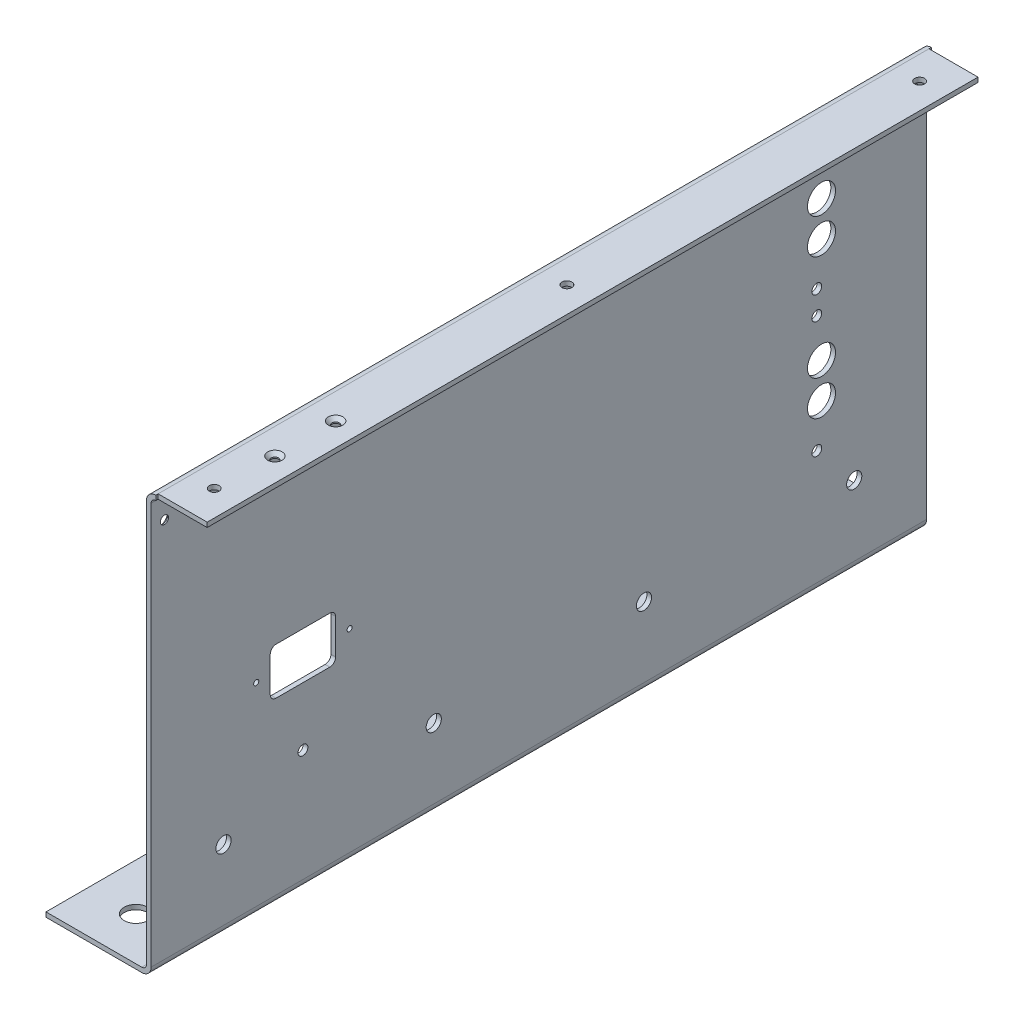
SolidWorks part; units mm, degrees
ref_plane "Спереди" through (0, 0, 0) normal (0, 0, 1) x (1, 0, 0)
ref_plane "Сверху" through (0, 0, 0) normal (0, 1, 0) x (1, 0, 0)
ref_plane "Справа" through (0, 0, 0) normal (1, 0, 0) x (0, 0, -1)
sketch "Эскиз1" plane through (0, 0, 0) normal (0, 0, 1) x (1, 0, 0)
  line L0 (0, 0) -> (0, 82.8028) construction
  line L1 (-1, -68) -> (-1, 104)
  line L4 (1, -68) -> (1, 104)
  line L5 (0, 0) -> (50.6989, 0) construction
  line L6 (3, 106) -> (24, 106)
  line L7 (3, 108) -> (24, 108)
  line L9 (-3, -72) -> (-44, -72)
  line L10 (24, 108) -> (24, 106)
  line L12 (-3, -70) -> (-44, -70)
  line L13 (-44, -72) -> (-44, -70)
  arc A0 (3, 106) -> (1, 104) centre (3, 104) ccw
  arc A1 (-3, -70) -> (-1, -68) centre (-3, -68) ccw
  arc A2 (-3, -72) -> (1, -68) centre (-3, -68) ccw
  arc A3 (-1, 104) -> (3, 108) centre (3, 104) cw
  dimension "D7" = 2
  dimension "D8" = 4
  dimension "D1" = 2
  dimension "D2" = 180
  dimension "D3" = 2
  dimension "D4" = 25
  dimension "D5" = 45
  dimension "D6" = 2
extrude "Вытянуть1" add sketch "Эскиз1" along normal blind 332
sketch "Эскиз2" plane through (-1, 0, 0) normal (-1, 0, 0) x (0, 0, 1)
  line L0 (-8.3976, -38) -> (341.3976, -38) construction
  line L1 (332, -72) -> (0, -72) construction
  line L2 (166, 127.3322) -> (166, -99.1297) construction
  line L3 (0, 104) -> (0, -68) construction
  line L4 (332, 104) -> (332, -68) construction
  circle A0 centre (31, -38) radius 3.25
  circle A1 centre (121, -38) radius 3.25
  circle A2 centre (211, -38) radius 3.25
  circle A3 centre (301, -38) radius 3.25
  dimension "D2" = 90
  dimension "D4" = 6.5
  dimension "D1" = 34
  dimension "D3" = 31
extrude "Вырез-Вытянуть1" cut sketch "Эскиз2" against normal blind 5
sketch "Эскиз3" plane through (0, -70, 0) normal (0, 1, 0) x (1, 0, 0)
  line L0 (-79.1329, -166) -> (76.6618, -166) construction
  line L1 (-24, 28.7881) -> (-24, -351.4381) construction
  line L4 (-44, -332) -> (-44, 0) construction
  line L5 (-3, 0) -> (-44, 0) construction
  line L6 (-3, -332) -> (-44, -332) construction
  circle A0 centre (-24, -18.5) radius 5
  circle A1 centre (-24, -313.5) radius 5
  dimension "D2" = 295
  dimension "D3" = 10
  dimension "D1" = 20
extrude "Вырез-Вытянуть2" cut sketch "Эскиз3" against normal blind 5
sketch "Эскиз4" plane through (0, 108, 0) normal (0, 1, 0) x (1, 0, 0)
  line L0 (-77.123, -166) -> (75.0406, -166) construction
  line L1 (24, 0) -> (3, 0) construction
  line L2 (24, -332) -> (3, -332) construction
  line L3 (3, -332) -> (3, 0) construction
  line L4 (3, -1) -> (29.1791, -1)
  line L5 (3, -1) -> (3, 2.2573)
  line L6 (3, 2.2573) -> (29.1791, 2.2573)
  line L7 (29.1791, -1) -> (29.1791, 2.2573)
  line L8 (24, -332) -> (24, 0) construction
  line L9 (29.1791, -331) -> (29.1791, -334.2573)
  line L10 (3, -334.2573) -> (29.1791, -334.2573)
  line L11 (3, -331) -> (3, -334.2573)
  line L12 (3, -331) -> (29.1791, -331)
  dimension "D1" = 1
  dimension "D2" = 21
extrude "Вырез-Вытянуть3" cut sketch "Эскиз4" against normal blind 10
sketch "Эскиз5" plane through (-1, 0, 0) normal (-1, 0, 0) x (0, 0, 1)
  line L0 (331, 108) -> (1, 108) construction
  line L1 (0, 104) -> (0, -68) construction
  line L2 (166, -112.0097) -> (166, 140.7956) construction
  line L3 (332, 104) -> (332, -68) construction
  circle A0 centre (5.7, 95) radius 1.75
  circle A1 centre (326.3, 95) radius 1.75
  dimension "D1" = 13
  dimension "D3" = 3.5
  dimension "D2" = 5.7
extrude "Вырез-Вытянуть4" cut sketch "Эскиз5" against normal blind 2.5
chamfer "Фаска1" distance 1.5 angle 45 2 edges at (-1, 96.75, 326.3) (-1, 93.25, 5.7)
sketch "Эскиз6" plane through (-1, 0, 0) normal (-1, 0, 0) x (0, 0, 1)
  line L0 (47, 93.2316) -> (47, -25.0596) construction
  line L1 (0, 104) -> (0, -68) construction
  line L2 (332, -70) -> (0, -70) construction
  line L3 (64.8276, 6) -> (25.4985, 6) construction
  line L4 (64.8276, 66) -> (25.4985, 66) construction
  line L5 (45, -11.328) -> (45, 71.6756) construction
  circle A0 centre (47, 91) radius 2.1
  circle A1 centre (47, 41) radius 2.1
  circle A2 centre (47, 31) radius 2.1
  circle A3 centre (47, -19) radius 2.1
  circle A4 centre (45, -1.5) radius 6
  circle A5 centre (45, 58.5) radius 6
  circle A6 centre (45, 13.5) radius 6
  circle A7 centre (45, 73.5) radius 6
  dimension "D2" = 50
  dimension "D3" = 50
  dimension "D5" = 10
  dimension "D6" = 4.2
  dimension "D8" = 7.5
  dimension "D9" = 7.5
  dimension "D10" = 12
  dimension "D1" = 47
  dimension "D4" = 161
  dimension "D7" = 2
extrude "Вырез-Вытянуть5" cut sketch "Эскиз6" against normal blind 10
cosmetic thread "Условное изображение резьбы1"
cosmetic thread "Условное изображение резьбы2"
cosmetic thread "Условное изображение резьбы3"
cosmetic thread "Условное изображение резьбы4"
sketch "Эскиз8" plane through (-1, 0, 0) normal (-1, 0, 0) x (0, 0, 1)
  line L0 (267, -27.9587) -> (267, 43.5369) construction
  line L1 (255.5, 5) -> (278.5, 5)
  line L2 (281, 22.5) -> (281, 7.5)
  line L3 (255.5, 25) -> (278.5, 25)
  line L4 (253, 22.5) -> (253, 7.5)
  line L5 (332, 104) -> (332, -68) construction
  line L6 (247, 15) -> (314.1741, 15) construction
  line L8 (332, -70) -> (0, -70) construction
  circle A0 centre (267, -20) radius 2.1
  arc A1 (255.5, 25) -> (253, 22.5) centre (255.5, 22.5) ccw
  arc A2 (281, 22.5) -> (278.5, 25) centre (278.5, 22.5) ccw
  arc A3 (255.5, 5) -> (253, 7.5) centre (255.5, 7.5) cw
  arc A4 (278.5, 5) -> (281, 7.5) centre (278.5, 7.5) ccw
  circle A5 centre (287, 15) radius 1.1
  circle A6 centre (247, 15) radius 1.1
  dimension "D4" = 2.5
  dimension "D6" = 2.5
  dimension "D9" = 2.2
  dimension "D10" = 4.2
  dimension "D11" = 50
  dimension "D1" = 28
  dimension "D2" = 40
  dimension "D3" = 10
  dimension "D5" = 20
  dimension "D7" = 85
  dimension "D8" = 65
extrude "Вырез-Вытянуть6" cut sketch "Эскиз8" against normal blind 10
cosmetic thread "Условное изображение резьбы8" parameters "D2"=5
cosmetic thread "Условное изображение резьбы9"
cosmetic thread "Условное изображение резьбы10"
sketch "Эскиз9" plane through (0, 108, 0) normal (0, 1, 0) x (1, 0, 0)
  line L0 (14, -323.3272) -> (14, -260.5986) construction
  line L1 (24, -331) -> (24, -1) construction
  line L3 (-3, -332) -> (-44, -332) construction
  circle A0 centre (14, -266) radius 1.6
  circle A1 centre (14, -292) radius 1.6
  dimension "D2" = 26
  dimension "D3" = 3.2
  dimension "D1" = 10
  dimension "D4" = 40
extrude "Вырез-Вытянуть7" cut sketch "Эскиз9" against normal blind 10
chamfer "Фаска2" distance 1.5 angle 45 2 edges at (14, 108, 267.6) (14, 108, 293.6)
sketch "Эскиз10" plane through (0, 108, 0) normal (0, 1, 0) x (1, 0, 0)
  line L0 (13, 17.8396) -> (13, -339.5207) construction
  line L1 (-79.7885, -166) -> (69.5643, -166) construction
  line L2 (-3, 0) -> (-44, 0) construction
  line L3 (-3, -332) -> (-44, -332) construction
  line L5 (-1, -332) -> (-1, 0) construction
  circle A0 centre (13, -15) radius 2.1
  circle A1 centre (13, -166) radius 2.1
  circle A2 centre (13, -317) radius 2.1
  dimension "D3" = 4.2
  dimension "D4" = 4.2
  dimension "D1" = 14
  dimension "D2" = 15
extrude "Вырез-Вытянуть8" cut sketch "Эскиз10" against normal blind 10
cosmetic thread "Условное изображение резьбы5"
cosmetic thread "Условное изображение резьбы6"
cosmetic thread "Условное изображение резьбы7"
